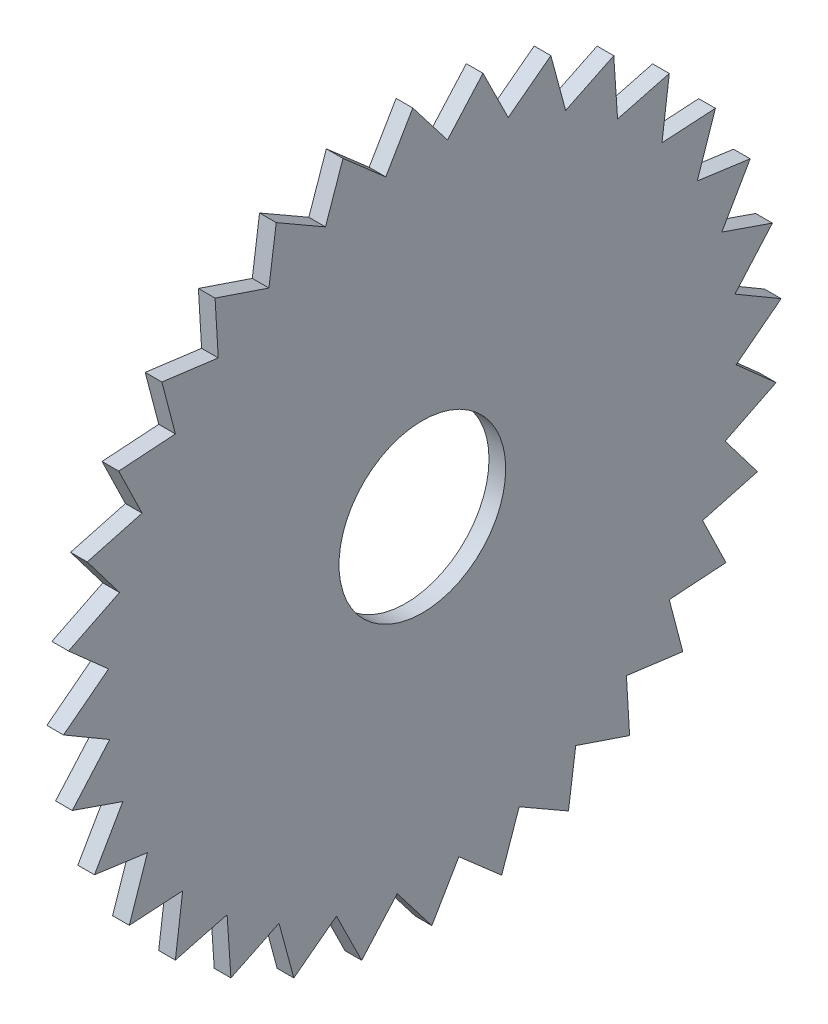
SolidWorks part; units mm, degrees
ref_plane "Front Plane" through (0, 0, 0) normal (0, 0, 1) x (1, 0, 0)
ref_plane "Top Plane" through (0, 0, 0) normal (0, 1, 0) x (1, 0, 0)
ref_plane "Right Plane" through (0, 0, 0) normal (1, 0, 0) x (0, 0, -1)
sketch "Sketch1" plane through (0, 0, 0) normal (1, 0, 0) x (0, 0, -1)
  circle A0 centre (0, 0) radius 45
  dimension "D1" = 90
extrude "Boss-Extrude1" add sketch "Sketch1" along normal blind 2
sketch "Sketch3" plane through (2, 0, 0) normal (1, 0, 0) x (0, 0, -1)
  line L0 (0, 45) -> (-4.3844, 37.5083)
  line L1 (-4.3844, 37.5083) -> (-11.3037, 43.5572)
  circle A1 centre (0, 0) radius 45 construction
extrude "Cut-Extrude2" cut sketch "Sketch3" against normal through all and the other way through all flip side to cut
ref_axis "Axis1" through (2, 0, 0) along (-1, 0, 0)
pattern_circular "CirPattern1" count 32 over 360 about axis through (2, 0, 0) along (-1, 0, 0) of "Cut-Extrude2"
sketch "Sketch4" plane through (2, 0, 0) normal (1, 0, 0) x (0, 0, -1)
  circle A0 centre (0, 0) radius 10
  dimension "D1" = 20
extrude "Cut-Extrude3" cut sketch "Sketch4" against normal blind 10
